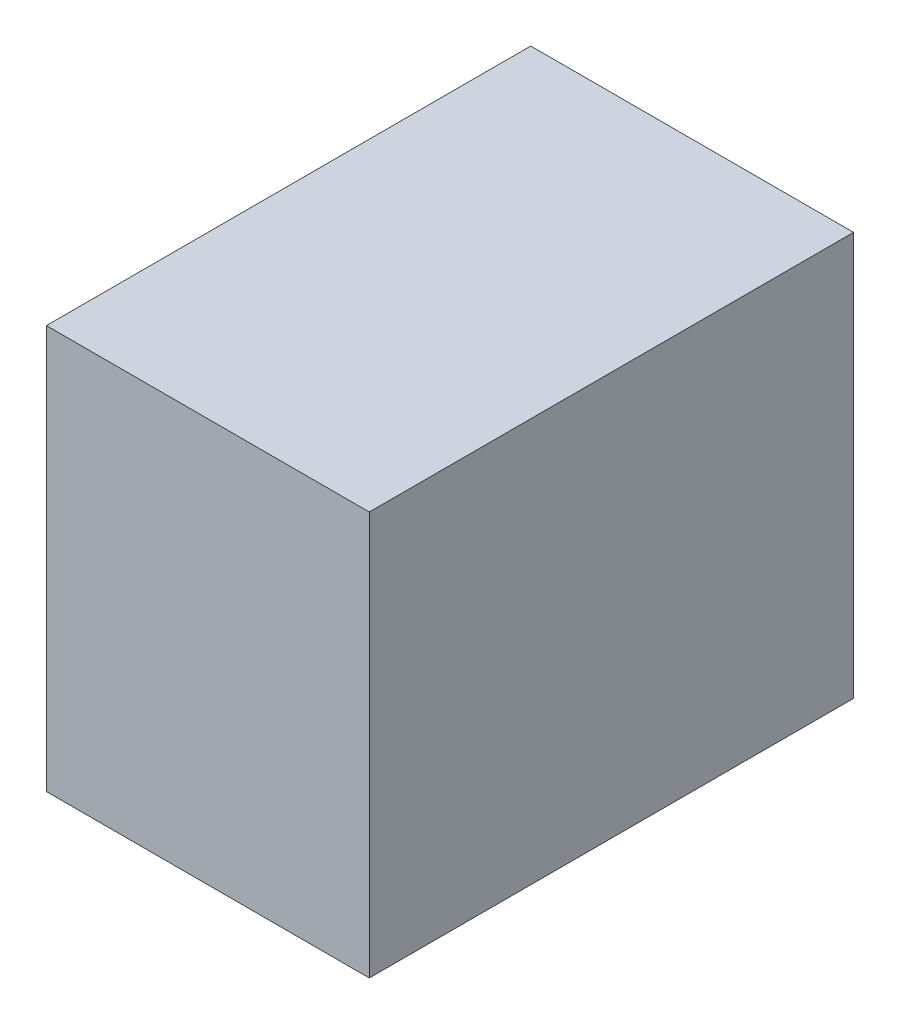
SolidWorks part; units mm, degrees
ref_plane "Front Plane" through (0, 0, 0) normal (0, 0, 1) x (1, 0, 0)
ref_plane "Top Plane" through (0, 0, 0) normal (0, 1, 0) x (1, 0, 0)
ref_plane "Right Plane" through (0, 0, 0) normal (1, 0, 0) x (0, 0, -1)
sketch "Sketch1" plane through (0, 0, 0) normal (0, 0, 1) x (1, 0, 0)
  line L1 (101.6, -127) -> (-101.6, -127)
  line L2 (101.6, -127) -> (101.6, 127)
  line L3 (101.6, 127) -> (-101.6, 127)
  line L4 (-101.6, -127) -> (-101.6, 127)
  line L5 (101.6, -127) -> (-101.6, 127) construction
  line L6 (101.6, 127) -> (-101.6, -127) construction
  point P0 (0, 0)
  dimension "D1" = 254
  dimension "D2" = 203.2
extrude "Boss-Extrude1" add sketch "Sketch1" along normal blind 304.8
